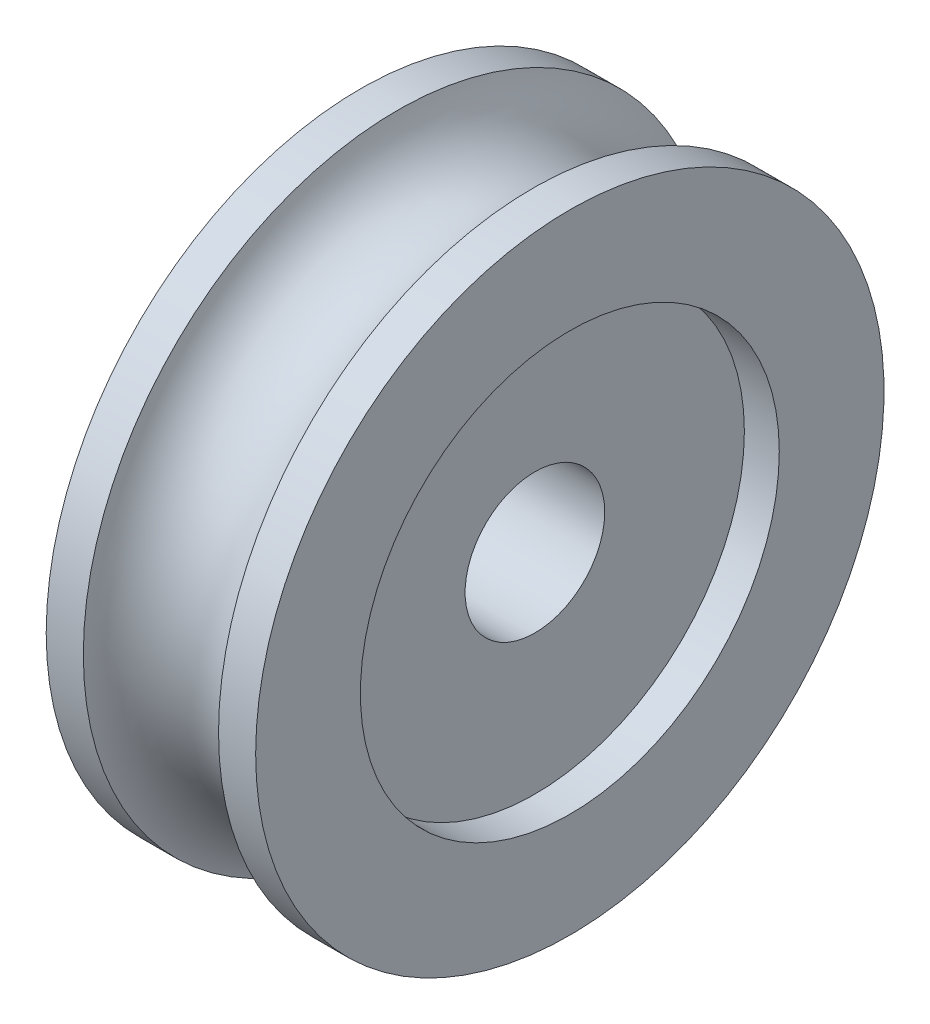
SolidWorks part; units mm, degrees
ref_plane "前视基准面" through (0, 0, 0) normal (0, 0, 1) x (1, 0, 0)
ref_plane "上视基准面" through (0, 0, 0) normal (0, 1, 0) x (1, 0, 0)
ref_plane "右视基准面" through (0, 0, 0) normal (1, 0, 0) x (0, 0, -1)
sketch "草图1" plane through (0, 0, 0) normal (0, 1, 0) x (1, 0, 0)
  line L0 (0, 5) -> (0, -4.5) construction
  line L1 (-3, 4.5) -> (3, 4.5) construction
  line L2 (-3, 4.5) -> (-3, -4.5)
  line L3 (-3, -4.5) -> (3, -4.5)
  line L4 (3, 4.5) -> (3, -4.5)
  line L5 (-3, 4.5) -> (3, -4.5) construction
  line L6 (-3, -4.5) -> (3, 4.5) construction
  line L7 (-1.9365, 4.5) -> (-3, 4.5)
  line L8 (1.9365, 4.5) -> (3, 4.5)
  line L9 (0, 3) -> (0, -4.5) construction
  circle A0 centre (0, 5) radius 2 construction
  arc A1 (-1.9365, 4.5) -> (1.9365, 4.5) centre (0, 5) ccw
  point P0 (0, 0)
  point P12 (0, 0)
  point P13 (0, 2.6572)
  point P14 (6.5, 6.5)
  point P15 (5.8183, 6.5)
  point P16 (6.5, 5.0405)
  point P17 (0, 1.7988)
  point P18 (0, 0)
  point P19 (0, 0)
  dimension "D3" = 4
  dimension "D1" = 9
  dimension "D2" = 6
  dimension "D4" = 7.5
revolve "旋转1" add sketch "草图1" angle 360 about L3
sketch "草图2" plane through (3, 0, 0) normal (1, 0, 0) x (0, 0, -1)
  circle A0 centre (-4.5, 0) radius 2
  dimension "D1" = 4
extrude "切除-拉伸1" cut sketch "草图2" against normal blind 55
sketch "草图3" plane through (3, 0, 0) normal (1, 0, 0) x (0, 0, -1)
  circle A0 centre (-4.5, 0) radius 6
  dimension "D1" = 12
extrude "切除-拉伸2" cut sketch "草图3" against normal blind 1
sketch "草图4" plane through (-3, 0, 0) normal (-1, 0, 0) x (0, 0, 1)
  circle A0 centre (4.5, 0) radius 6
  dimension "D1" = 12
extrude "切除-拉伸3" cut sketch "草图4" against normal blind 1
